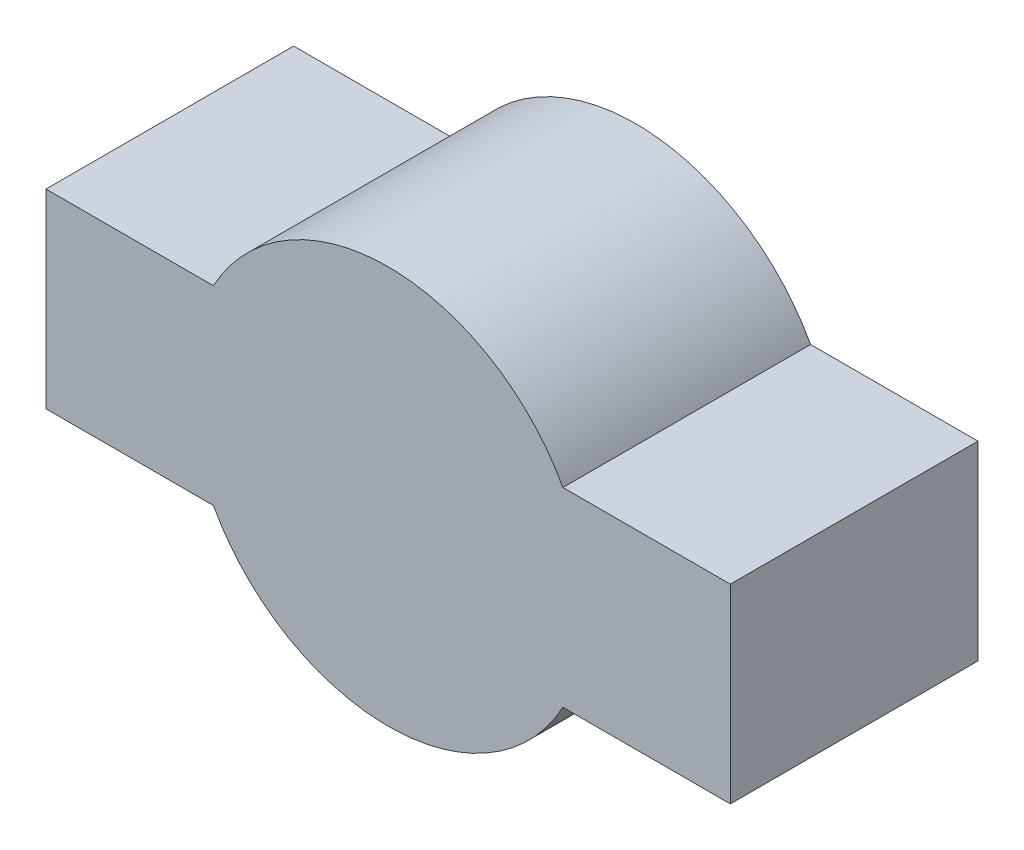
SolidWorks part; units mm, degrees
ref_plane "前视基准面" through (0, 0, 0) normal (0, 0, 1) x (1, 0, 0)
ref_plane "上视基准面" through (0, 0, 0) normal (0, 1, 0) x (1, 0, 0)
ref_plane "右视基准面" through (0, 0, 0) normal (1, 0, 0) x (0, 0, -1)
other "Configuration Table"
sketch "草图1" plane through (0, 0, 0) normal (0, 0, 1) x (1, 0, 0)
  line L1 (-138.1543, -38.427) -> (138.1543, -38.427)
  line L2 (-138.1543, -38.427) -> (-138.1543, 38.427)
  line L3 (-138.1543, 38.427) -> (138.1543, 38.427)
  line L4 (138.1543, -38.427) -> (138.1543, 38.427)
  line L5 (-138.1543, -38.427) -> (138.1543, 38.427) construction
  line L6 (-138.1543, 38.427) -> (138.1543, -38.427) construction
  circle A0 centre (0, 0) radius 80.3482
  point P0 (0, 0)
extrude "凸台-拉伸1" add sketch "草图1" along normal blind 100 contours L3 L4 L1 L2 | A0
sketch3d "3D草图2"
  point P0 (-0.6245, 80.3458, 53.2381)
  point P1 (-29.6263, 74.6868, 75.646)
  point P2 (-41.4415, 68.8363, 43.1793)
  point P3 (-61.2503, 52.0022, 18.6353)
  point P4 (-55.8888, 57.7259, 80.4122)
  point P5 (-16.1283, 78.7128, 86.6406)
  point P6 (53.4565, 59.9853, 51.5615)
  point P7 (19.895, 77.8461, 27.5197)
  point P8 (138.1543, 38.427, 100)
  point P9 (70.5634, 38.427, 0)
  point P11 (138.1543, -38.427, 0)
  point P13 (138.1543, -38.427, 100)
